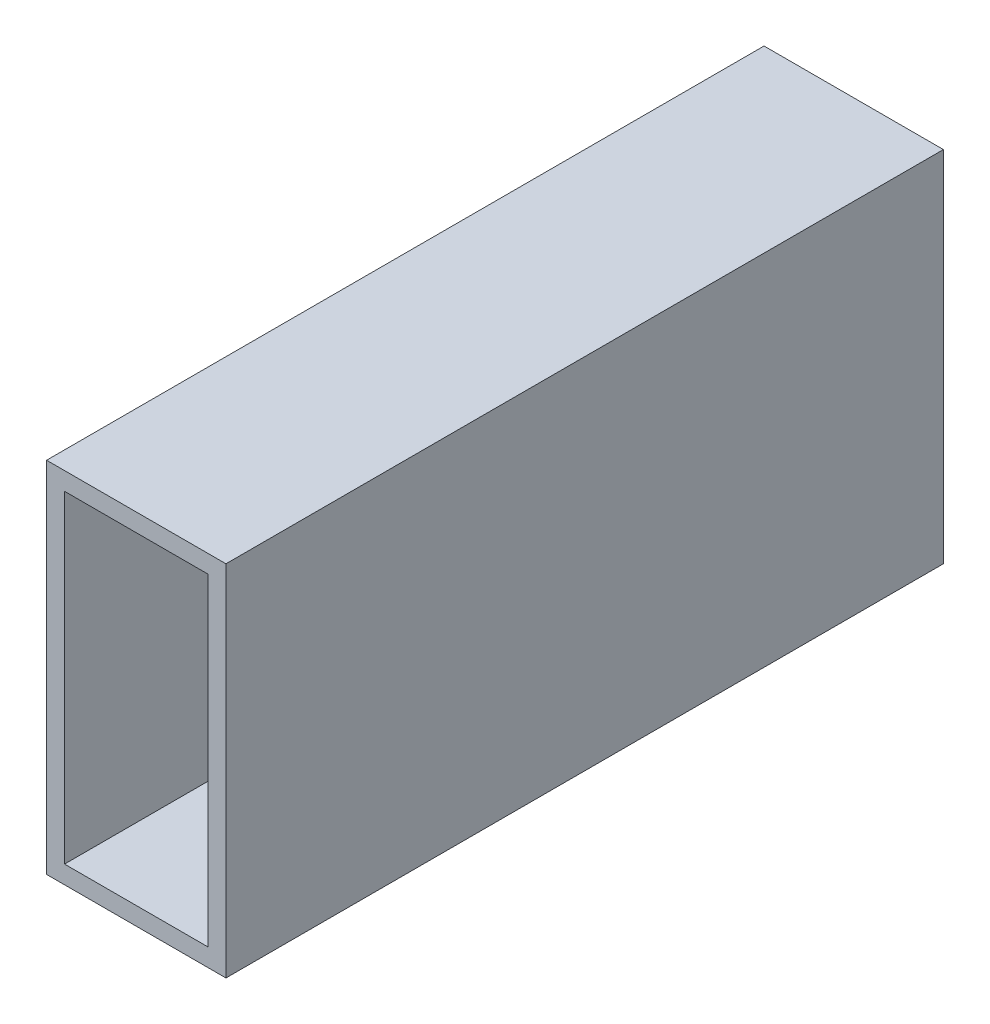
SolidWorks part; units mm, degrees
ref_plane "Front Plane" through (0, 0, 0) normal (0, 0, 1) x (1, 0, 0)
ref_plane "Top Plane" through (0, 0, 0) normal (0, 1, 0) x (1, 0, 0)
ref_plane "Right Plane" through (0, 0, 0) normal (1, 0, 0) x (0, 0, -1)
sketch "Sketch1" plane through (0, 0, 0) normal (0, 0, 1) x (1, 0, 0)
  line L1 (-12.5, 25) -> (12.5, 25)
  line L2 (-12.5, 25) -> (-12.5, -25)
  line L3 (-12.5, -25) -> (12.5, -25)
  line L4 (12.5, 25) -> (12.5, -25)
  line L5 (-12.5, 25) -> (12.5, -25) construction
  line L6 (-12.5, -25) -> (12.5, 25) construction
  line L7 (-10, 22.5) -> (10, 22.5)
  line L8 (-10, 22.5) -> (-10, -22.5)
  line L9 (-10, -22.5) -> (10, -22.5)
  line L10 (10, 22.5) -> (10, -22.5)
  line L11 (-10, 22.5) -> (10, -22.5) construction
  line L12 (-10, -22.5) -> (10, 22.5) construction
  point P0 (0, 0)
  point P6 (0, 0)
  dimension "D1" = 50
  dimension "D2" = 25
  dimension "D3" = 2.5
  dimension "D4" = 2.5
extrude "Boss-Extrude1" add sketch "Sketch1" along normal blind 100
